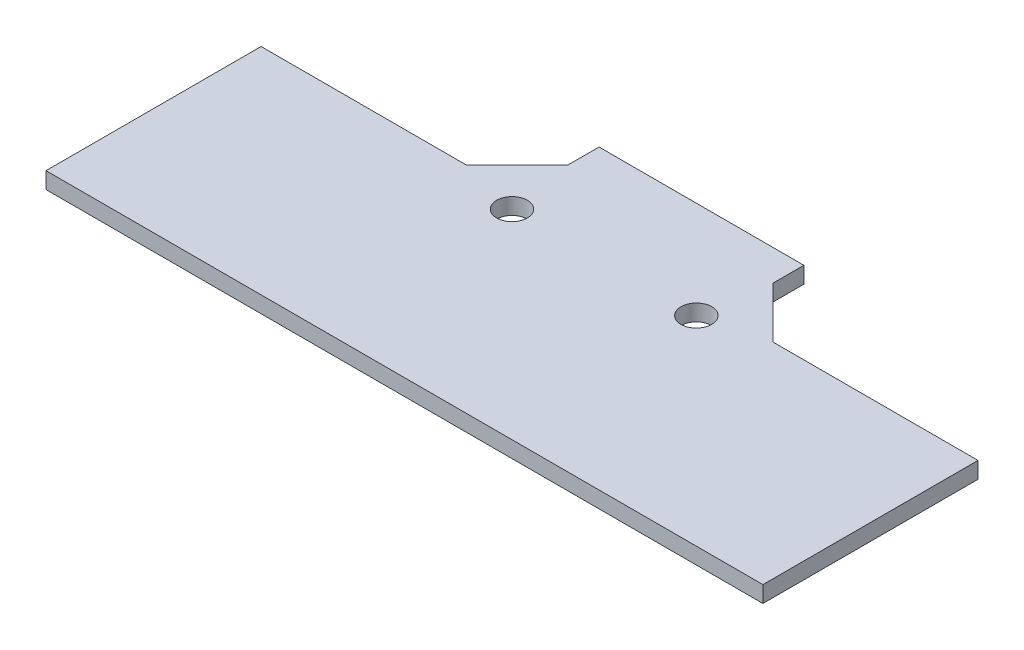
SolidWorks part; units mm, degrees
ref_plane "前视基准面" through (0, 0, 0) normal (0, 0, 1) x (1, 0, 0)
ref_plane "上视基准面" through (0, 0, 0) normal (0, 1, 0) x (1, 0, 0)
ref_plane "右视基准面" through (0, 0, 0) normal (1, 0, 0) x (0, 0, -1)
sketch "草图1" plane through (0, 0, 0) normal (0, 1, 0) x (1, 0, 0)
  line L0 (-9.7016, 20.6456) -> (-14.7016, 15.6456)
  line L1 (-34.7016, 15.6456) -> (-14.7016, 15.6456)
  line L2 (-34.7016, 15.6456) -> (-34.7016, -5.3544)
  line L3 (-34.7016, -5.3544) -> (35.2984, -5.3544)
  line L4 (35.2984, 15.6456) -> (35.2984, -5.3544)
  line L5 (-9.7016, 15.6456) -> (-8.7016, 15.6456)
  line L6 (-9.7016, 20.6456) -> (-9.7016, 23.6456)
  line L7 (-9.7016, 23.6456) -> (10.2984, 23.6456)
  line L8 (10.2984, 20.6456) -> (10.2984, 23.6456)
  line L17 (10.2984, 20.6456) -> (15.2984, 15.6456)
  line L18 (15.2984, 15.6456) -> (35.2984, 15.6456)
  line L19 (9.2984, 15.6456) -> (10.2984, 15.6456)
  line L20 (9.2984, 15.6456) -> (10.2984, 15.6456)
  line L21 (-9.7016, 15.6456) -> (-8.7016, 15.6456)
  circle A0 centre (-8.7016, 14.1456) radius 1.5
  circle A1 centre (9.2984, 14.1456) radius 1.5
  point P8 (0.2984, -5.3544)
  dimension "D3" = 19.5
  dimension "D4" = 19.5
  dimension "D1" = 70
  dimension "D2" = 21
  dimension "D5" = 18
  dimension "D6" = 9
  dimension "D7" = 8
  dimension "D8" = 20
  dimension "D9" = 25
extrude "凸台-拉伸1" add sketch "草图1" along normal blind 1.6
